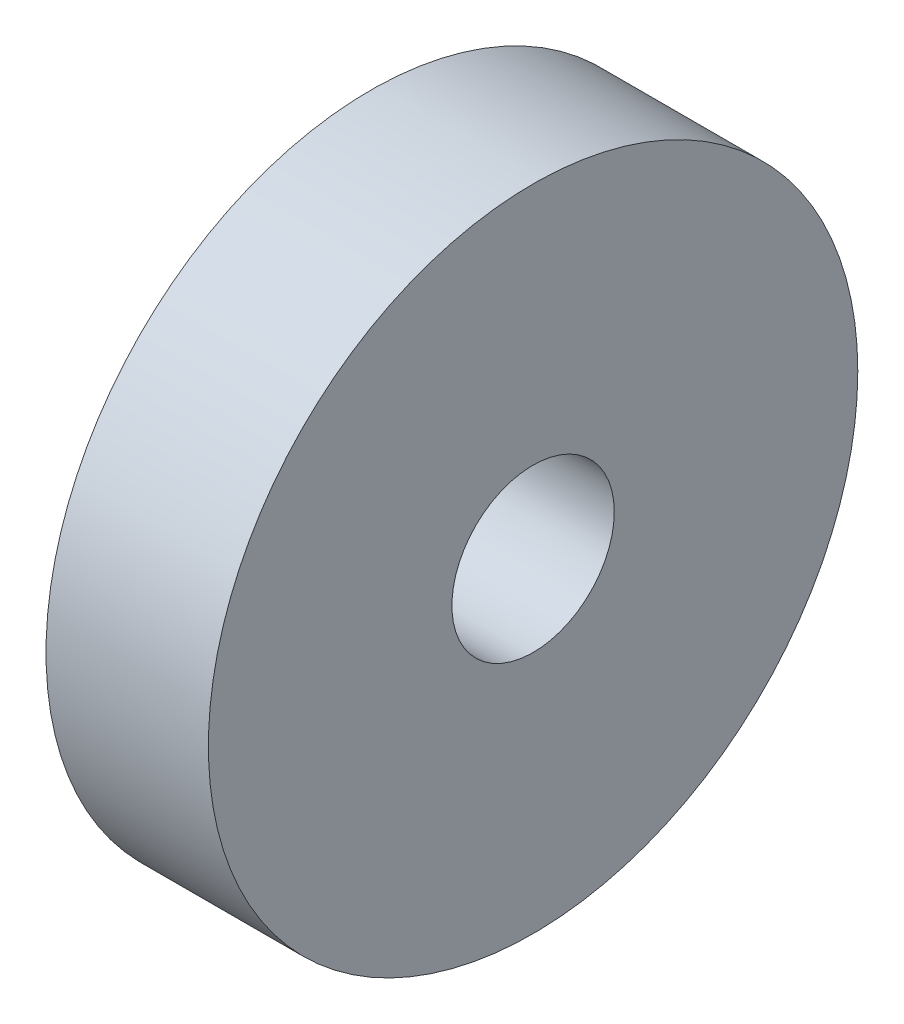
SolidWorks part; units mm, degrees
material "NBR"
ref_plane "前视基准面" through (0, 0, 0) normal (0, 0, 1) x (1, 0, 0)
ref_plane "上视基准面" through (0, 0, 0) normal (0, 1, 0) x (1, 0, 0)
ref_plane "右视基准面" through (0, 0, 0) normal (1, 0, 0) x (0, 0, -1)
sketch "草图1" plane through (0, 0, 0) normal (1, 0, 0) x (0, 0, -1)
  circle A0 centre (0, 0) radius 100
  circle A1 centre (0, 0) radius 25
  dimension "D1" = 200
  dimension "D2" = 50
extrude "凸台-拉伸1" add sketch "草图1" along normal blind 50
